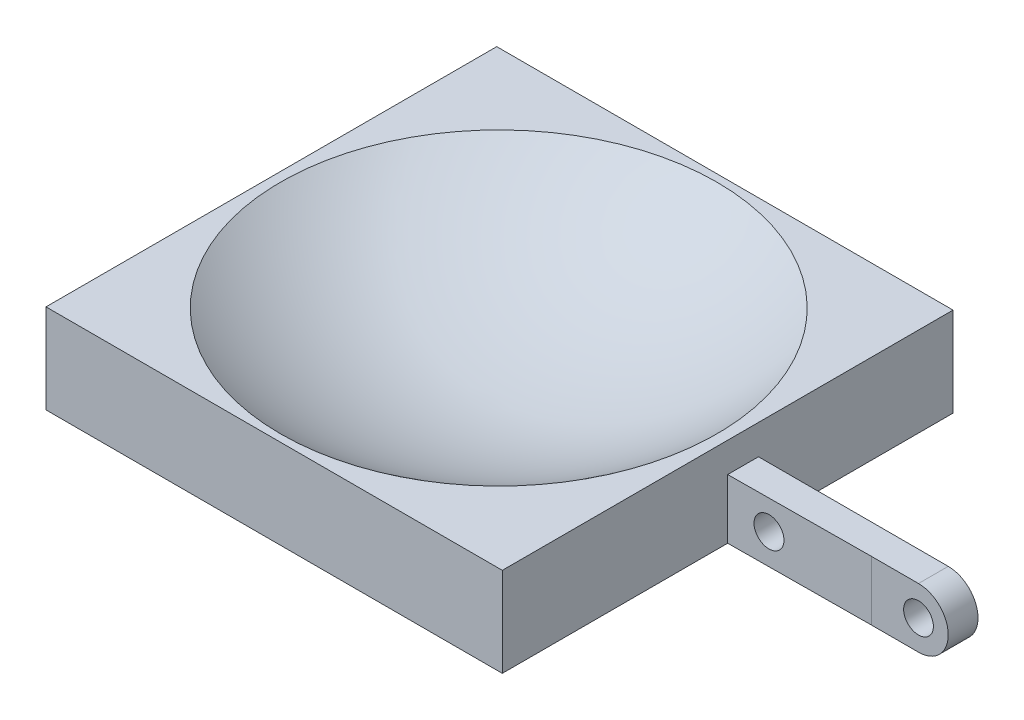
SolidWorks part; units mm, degrees
ref_plane "前视基准面" through (0, 0, 0) normal (0, 0, 1) x (1, 0, 0)
ref_plane "上视基准面" through (0, 0, 0) normal (0, 1, 0) x (1, 0, 0)
ref_plane "右视基准面" through (0, 0, 0) normal (1, 0, 0) x (0, 0, -1)
sketch "草图1" plane through (0, 0, 0) normal (0, 0, 1) x (1, 0, 0)
  line L0 (-217.9111, 17.3665) -> (-57.9111, 17.3665)
  line L1 (-217.9111, -2.6335) -> (-57.9111, -2.6335)
  line L2 (-217.9111, 17.3665) -> (-217.9111, -2.6335)
  arc A0 (-57.9111, 17.3665) -> (-57.9111, -2.6335) centre (-57.9111, 7.3665) cw
  dimension "D1" = 160
  dimension "D2" = 20
extrude "凸台-拉伸1" add sketch "草图1" along normal blind 10
sketch "草图2" plane through (0, 0, 10) normal (0, 0, 1) x (1, 0, 0)
  circle A0 centre (-57.9111, 7.3665) radius 5
  circle A1 centre (-7.9113, 7.2195) radius 5
  dimension "D1" = 50
extrude "切除-拉伸1" cut sketch "草图2" against normal blind 10
sketch "草图3" plane through (0, -2.6335, 0) normal (0, -1, 0) x (1, 0, 0)
  line L1 (-323.6529, 135.3523) -> (-73.6529, 135.3523)
  line L2 (-323.6529, 135.3523) -> (-323.6529, -114.6477)
  line L3 (-323.6529, -114.6477) -> (-73.6529, -114.6477)
  line L4 (-73.6529, 135.3523) -> (-73.6529, -114.6477)
extrude "凸台-拉伸2" add sketch "草图3" against normal blind 125 contours L2 L1 L4 L3
sketch "草图4" plane through (0, 122.3665, 0) normal (0, 1, 0) x (1, 0, 0)
  line L0 (-283.5057, 74.5005) -> (-113.8001, -95.2051)
  arc A1 (-113.8001, -95.2051) -> (-283.5057, 74.5005) centre (-198.6529, -10.3523) cw
revolve "切除-旋转1" cut sketch "草图4" angle 360 about L0
sketch "草图5" plane through (0, 122.3665, 0) normal (0, 1, 0) x (1, 0, 0)
  line L1 (-323.6529, 114.6477) -> (-73.6529, 114.6477)
  line L2 (-323.6529, 114.6477) -> (-323.6529, -135.3523)
  line L3 (-323.6529, -135.3523) -> (-73.6529, -135.3523)
  line L4 (-73.6529, 114.6477) -> (-73.6529, -135.3523)
extrude "切除-拉伸2" cut sketch "草图5" against normal blind 95
sketch "草图8" plane through (0, 27.3665, 0) normal (0, 1, 0) x (1, 0, 0)
  line L1 (-275.0698, 65.395) -> (-121.6983, 65.395)
  line L2 (-275.0698, 65.395) -> (-275.0698, -86.0996)
  line L3 (-275.0698, -86.0996) -> (-121.6983, -86.0996)
  line L4 (-121.6983, 65.395) -> (-121.6983, -86.0996)
  line L5 (-323.6529, 114.6477) -> (-73.6529, 114.6477)
  line L6 (-323.6529, 114.6477) -> (-323.6529, -135.3523)
  line L7 (-323.6529, -135.3523) -> (-73.6529, -135.3523)
  line L8 (-73.6529, 114.6477) -> (-73.6529, -135.3523)
extrude "切除-拉伸4" cut sketch "草图8" against normal blind 10
sketch "草图9" plane through (0, 17.3665, 0) normal (0, 1, 0) x (1, 0, 0)
  line L0 (-275.0698, 65.395) -> (-275.0698, -86.0996)
  line L1 (-275.0698, -86.0996) -> (-121.6983, -86.0996)
  line L2 (-121.6983, -86.0996) -> (-121.6983, -10.3523)
  line L3 (-121.6983, -86.0996) -> (-121.6983, 65.395) construction
  line L5 (-47.9111, -10) -> (-47.9111, 0)
  line L7 (-121.6983, 0) -> (-121.6983, 65.395)
  line L8 (-121.6983, 65.395) -> (-275.0698, 65.395)
  line L9 (-121.6983, -10.3523) -> (-73.6529, -10)
  line L10 (-73.6529, -10) -> (-73.6529, -135.3523)
  line L11 (-73.6529, -135.3523) -> (-323.6529, -135.3523)
  line L12 (-323.6529, -135.3523) -> (-323.6529, 114.6477)
  line L13 (-323.6529, 114.6477) -> (-73.6529, 114.6477)
  line L14 (-73.6529, 114.6477) -> (-73.6529, 0)
  line L15 (-73.6529, 0) -> (-121.6983, 0)
  line M2 (-73.6529, 0) -> (-73.6529, 114.6477)
  line M3 (-73.6529, 114.6477) -> (-323.6529, 114.6477)
  line M4 (-323.6529, 114.6477) -> (-323.6529, -135.3523)
  line M5 (-323.6529, -135.3523) -> (-73.6529, -135.3523)
  line M6 (-73.6529, -135.3523) -> (-73.6529, -10)
  line M9 (-275.0698, 65.395) -> (-121.6983, 65.395)
  line M10 (-121.6983, 65.395) -> (-121.6983, -86.0996)
  line M11 (-121.6983, -86.0996) -> (-275.0698, -86.0996)
  line M12 (-275.0698, -86.0996) -> (-275.0698, 65.395)
extrude "切除-拉伸5" cut sketch "草图9" against normal through all contours L15 L9 M2 M3 M4 M5 M6 M10 M11 M12 M9
sketch "草图10" plane through (0, 0, 10) normal (0, 0, 1) x (1, 0, 0)
  circle A0 centre (-107.9108, 7.5542) radius 5
  circle A1 centre (-57.9111, 7.3665) radius 5 construction
  point P4 (-55.6248, 7.6414)
  point P5 (0, 0)
  point P6 (-43.2464, 8.7571)
  point P7 (-55.6264, 7.2776)
  point P8 (-107.91, 7.6966)
  point P9 (-107.9096, 6.9757)
  point P10 (-107.9097, 7.7471)
  point P11 (-107.9097, 7.7471)
  point P12 (-107.9096, 6.9787)
  point P13 (-107.9108, 7.5542)
  dimension "D1" = 50
extrude "切除-拉伸7" cut sketch "草图10" against normal through all
sketch "草图12" plane through (0, 0, 10) normal (0, 0, -1) x (-1, 0, 0)
  circle A0 centre (107.9108, 7.5542) radius 5
extrude "切除-拉伸8" cut sketch "草图12" against normal through all
